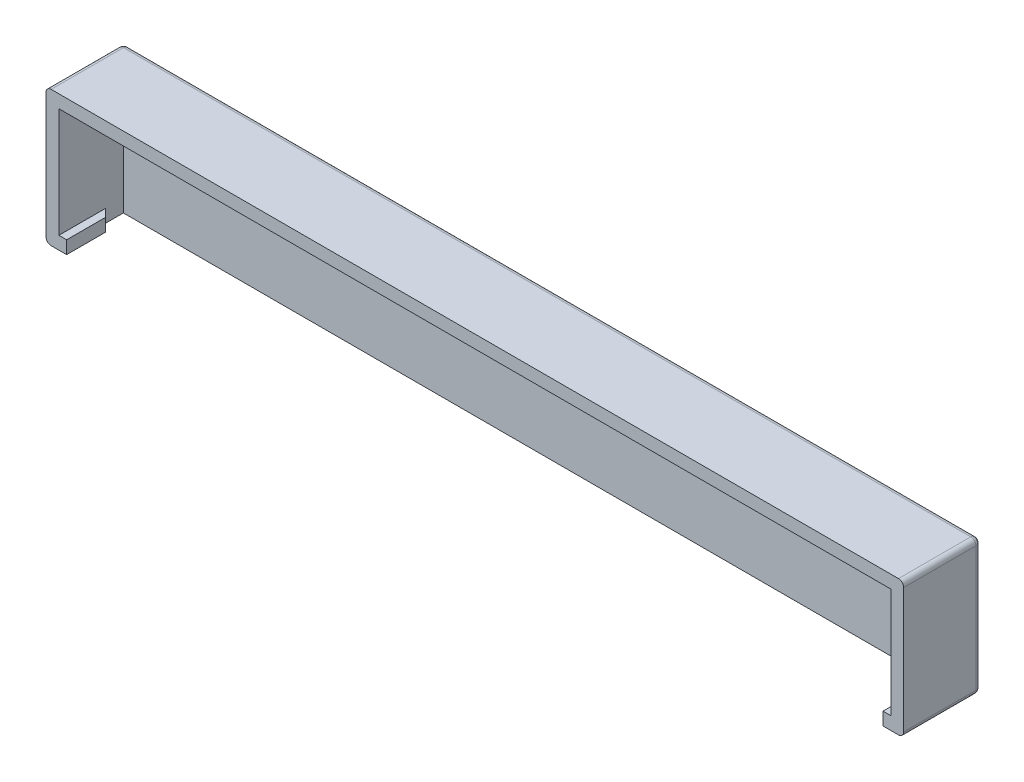
SolidWorks part; units mm, degrees
ref_plane "Front Plane" through (0, 0, 0) normal (0, 0, 1) x (1, 0, 0)
ref_plane "Top Plane" through (0, 0, 0) normal (0, 1, 0) x (1, 0, 0)
ref_plane "Right Plane" through (0, 0, 0) normal (1, 0, 0) x (0, 0, -1)
sketch "Sketch1" plane through (0, 0, 0) normal (0, 0, 1) x (1, 0, 0)
  line L1 (0, 0) -> (211.1375, 0)
  line L2 (0, 0) -> (0, 33.3375)
  line L3 (0, 33.3375) -> (211.1375, 33.3375)
  line L4 (211.1375, 0) -> (211.1375, 33.3375)
  dimension "D1" = 211.1375
  dimension "D2" = 33.3375
extrude "Boss-Extrude1" add sketch "Sketch1" along normal blind 3.175 contours L3 L4 L1 L2
sketch "Sketch2" plane through (0, 0, 3.175) normal (0, 0, 1) x (1, 0, 0)
  line L11 (5.08, 0) -> (5.08, 3.175)
  line L12 (206.0575, 0) -> (206.0575, 3.175)
  line L13 (0, 0) -> (5.08, 0)
  line L14 (206.0575, 3.175) -> (207.9625, 3.175)
  line L15 (207.9625, 3.175) -> (207.9625, 30.1625)
  line L16 (3.175, 3.175) -> (207.9625, 3.175)
  line L17 (3.175, 30.1625) -> (3.175, 3.175)
  line L18 (207.9625, 30.1625) -> (3.175, 30.1625)
  line L19 (207.9625, 3.175) -> (207.9625, 30.1625)
  line L20 (3.175, 3.175) -> (5.08, 3.175)
  line L21 (3.175, 30.1625) -> (3.175, 3.175)
  line L22 (207.9625, 30.1625) -> (3.175, 30.1625)
  line L23 (0, 33.3375) -> (0, 0)
  line L24 (0, 0) -> (211.1375, 0)
  line L25 (211.1375, 0) -> (211.1375, 33.3375)
  line L26 (211.1375, 33.3375) -> (0, 33.3375)
  line L27 (0, 33.3375) -> (0, 0)
  line L28 (206.0575, 0) -> (211.1375, 0)
  line L29 (211.1375, 0) -> (211.1375, 33.3375)
  line L30 (211.1375, 33.3375) -> (0, 33.3375)
  point P9 (5.08, 1.5875)
  dimension "D3" = 5.08
  dimension "D4" = 5.08
  dimension "D1" = 3.175
  dimension "D2" = 0
extrude "Boss-Extrude2" add sketch "Sketch2" along direction (0, 0, -1) on the side of the normal offset from surface (15.875 mm away) 19.05
sketch "Sketch3" plane through (0, 0, 0) normal (0, -1, 0) x (1, 0, 0)
  line L0 (207.9625, 19.05) -> (207.9625, 3.175) construction
  line L2 (207.9625, 19.05) -> (207.9625, 3.175) construction
  line L3 (105.5688, 19.05) -> (105.5688, 0) construction
  line L4 (207.9625, 19.05) -> (3.175, 19.05) construction
  line L5 (207.9625, 3.175) -> (206.0575, 3.175)
  line L6 (206.0575, 3.175) -> (206.0575, 9.525)
  line L7 (206.0575, 19.05) -> (206.0575, 3.175) construction
  line L8 (206.0575, 9.525) -> (207.9625, 7.62)
  line L9 (207.9625, 7.62) -> (207.9625, 3.175)
  line L10 (0, 0) -> (211.1375, 0) construction
  line L11 (5.08, 9.525) -> (3.175, 7.62)
  line L12 (5.08, 3.175) -> (5.08, 9.525)
  line L13 (3.175, 3.175) -> (5.08, 3.175)
  line L14 (3.175, 7.62) -> (3.175, 3.175)
  point P19 (0, 0)
  point P20 (0, 0)
  dimension "D1" = 135
  dimension "D2" = 6.35
extrude "Cut-Extrude1" cut sketch "Sketch3" against normal up to next
fillet "Fillet1" radius 1.27 8 edges at (105.5688, 0, 0) (0, 0, 9.525) (0, 16.6687, 0) (0, 33.3375, 9.525) (105.5688, 33.3375, 0) (211.1375, 16.6687, 0) (211.1375, 0, 9.525) (211.1375, 33.3375, 9.525)
